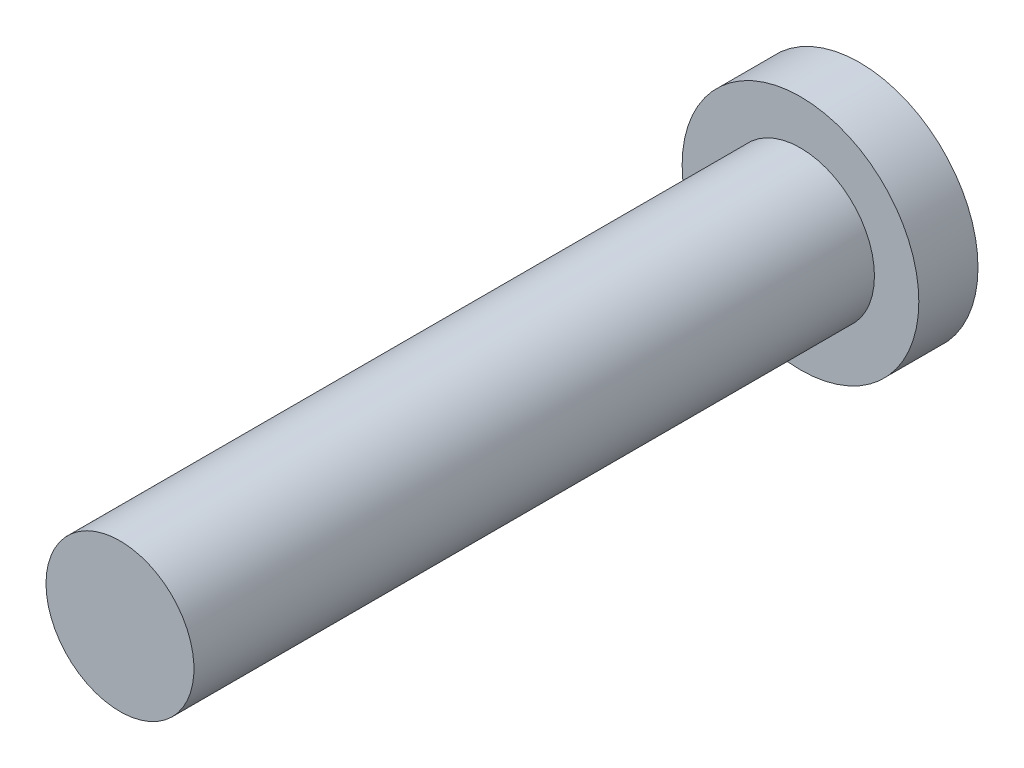
SolidWorks part; units mm, degrees
ref_plane "Přední rovina" through (0, 0, 0) normal (0, 0, 1) x (1, 0, 0)
ref_plane "Horní rovina" through (0, 0, 0) normal (0, 1, 0) x (1, 0, 0)
ref_plane "Pravá rovina" through (0, 0, 0) normal (1, 0, 0) x (0, 0, -1)
sketch "Skica1" plane through (0, 0, 0) normal (0, 0, 1) x (1, 0, 0)
  circle A0 centre (0, 0) radius 4
  dimension "D1" = 8
extrude "Přidat vysunutím2" add sketch "Skica1" along normal blind 2
sketch "Skica2" plane through (0, 0, 0) normal (0, 0, -1) x (-1, 0, 0)
  circle A0 centre (0, 0) radius 2.5
  dimension "D1" = 5
extrude "Přidat vysunutím3" add sketch "Skica2" against normal blind 25
